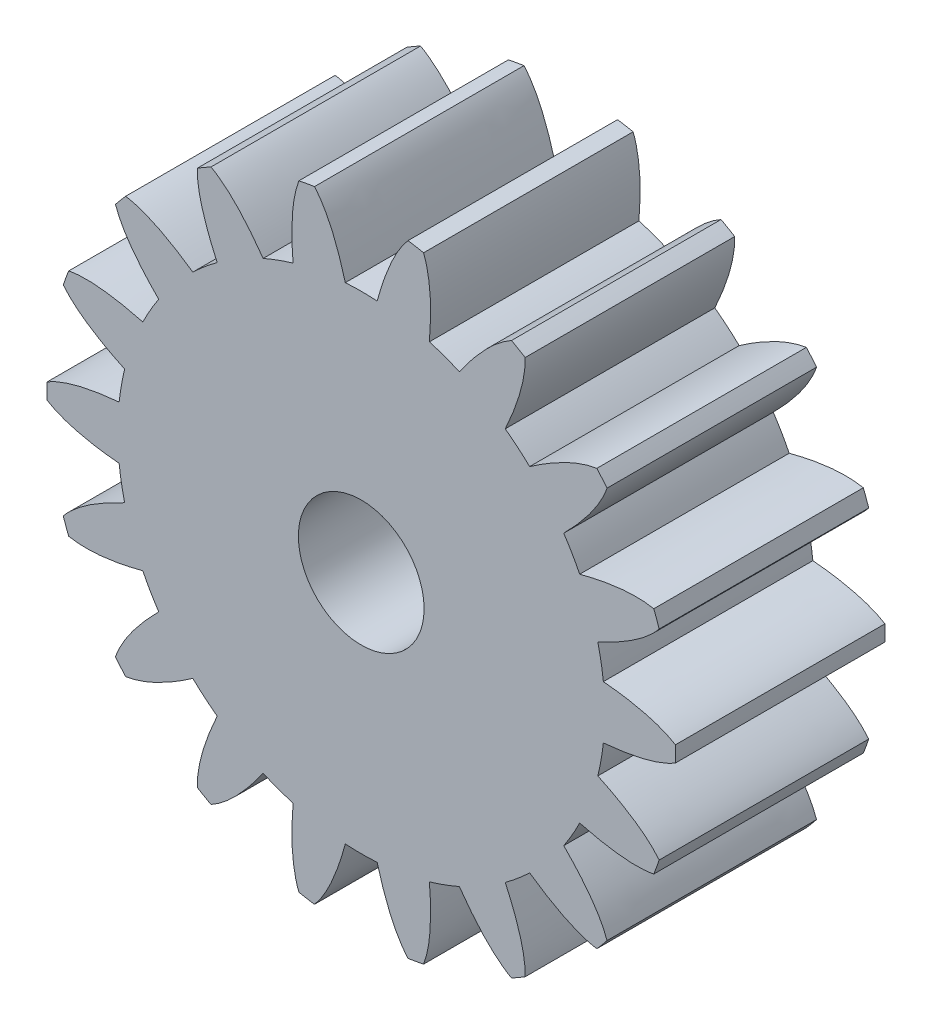
SolidWorks part; units mm, degrees
material "Plain Carbon Steel"
ref_plane "Front Plane" through (0, 0, 0) normal (0, 0, 1) x (1, 0, 0)
ref_plane "Top Plane" through (0, 0, 0) normal (0, 1, 0) x (1, 0, 0)
ref_plane "Right Plane" through (0, 0, 0) normal (1, 0, 0) x (0, 0, -1)
sketch "Sketch2" plane through (0, 0, 0) normal (0, 0, 1) x (1, 0, 0)
  line L0 (-2.6047, 14.7721) -> (-2.0185, 11.4474) construction
  arc A0 (-3.253, 11.1595) -> (-4.6813, 10.6397) centre (0, 0) ccw
  arc A1 (-2.2327, 14.8329) -> (-2.9751, 14.702) centre (0, 0) ccw
  arc A2 (2.9751, 14.702) -> (2.2327, 14.8329) centre (0, 0) ccw
  arc A3 (7.8241, 12.7978) -> (7.1712, 13.1748) centre (0, 0) ccw
  arc A4 (11.7293, 9.35) -> (11.2447, 9.9275) centre (0, 0) ccw
  arc A5 (14.2199, 4.7745) -> (13.962, 5.4829) centre (0, 0) ccw
  arc A6 (14.9953, -0.377) -> (14.9953, 0.377) centre (0, 0) ccw
  arc A7 (13.962, -5.4829) -> (14.2199, -4.7745) centre (0, 0) ccw
  arc A8 (11.2447, -9.9275) -> (11.7293, -9.35) centre (0, 0) ccw
  arc A9 (7.1712, -13.1748) -> (7.8241, -12.7978) centre (0, 0) ccw
  arc A10 (2.2327, -14.8329) -> (2.9751, -14.702) centre (0, 0) ccw
  arc A11 (-2.9751, -14.702) -> (-2.2327, -14.8329) centre (0, 0) ccw
  arc A12 (-7.8241, -12.7978) -> (-7.1712, -13.1748) centre (0, 0) ccw
  arc A13 (-11.7293, -9.35) -> (-11.2447, -9.9275) centre (0, 0) ccw
  arc A14 (-14.2199, -4.7745) -> (-13.962, -5.4829) centre (0, 0) ccw
  arc A15 (-14.9953, 0.377) -> (-14.9953, -0.377) centre (0, 0) ccw
  arc A16 (-13.962, 5.4829) -> (-14.2199, 4.7745) centre (0, 0) ccw
  arc A17 (-11.2447, 9.9275) -> (-11.7293, 9.35) centre (0, 0) ccw
  arc A18 (-7.1712, 13.1748) -> (-7.8241, 12.7978) centre (0, 0) ccw
  arc A19 (-6.8736, 9.374) -> (-8.038, 8.3969) centre (0, 0) ccw
  arc A20 (-9.6652, 6.4577) -> (-10.4251, 5.1414) centre (0, 0) ccw
  arc A21 (-11.2909, 2.7626) -> (-11.5549, 1.2657) centre (0, 0) ccw
  arc A22 (-11.5549, -1.2657) -> (-11.2909, -2.7626) centre (0, 0) ccw
  arc A23 (-10.4251, -5.1414) -> (-9.6652, -6.4577) centre (0, 0) ccw
  arc A24 (-8.038, -8.3969) -> (-6.8736, -9.374) centre (0, 0) ccw
  arc A25 (-4.6813, -10.6397) -> (-3.253, -11.1595) centre (0, 0) ccw
  arc A26 (-0.76, -11.5991) -> (0.76, -11.5991) centre (0, 0) ccw
  arc A27 (3.253, -11.1595) -> (4.6813, -10.6397) centre (0, 0) ccw
  arc A28 (6.8736, -9.374) -> (8.038, -8.3969) centre (0, 0) ccw
  arc A29 (9.6652, -6.4577) -> (10.4251, -5.1414) centre (0, 0) ccw
  arc A30 (11.2909, -2.7626) -> (11.5549, -1.2657) centre (0, 0) ccw
  arc A31 (11.5549, 1.2657) -> (11.2909, 2.7626) centre (0, 0) ccw
  arc A32 (10.4251, 5.1414) -> (9.6652, 6.4577) centre (0, 0) ccw
  arc A33 (8.038, 8.3969) -> (6.8736, 9.374) centre (0, 0) ccw
  arc A34 (4.6813, 10.6397) -> (3.253, 11.1595) centre (0, 0) ccw
  arc A35 (0.76, 11.5991) -> (-0.76, 11.5991) centre (0, 0) ccw
  circle A36 centre (0, 0) radius 3
  spline S0 degree 2 poles (-2.9751, 14.702) (-3.4475, 13.4911) (-3.253, 11.1595) knots 0 0 0 0.715421 0.715421 0.715421
  spline S1 degree 2 poles (-2.2327, 14.8329) (-1.3746, 13.8566) (-0.76, 11.5991) knots 0 0 0 0.715421 0.715421 0.715421
  spline S2 degree 2 poles (2.2327, 14.8329) (1.3746, 13.8566) (0.76, 11.5991) knots 0 0 0 0.715421 0.715421 0.715421
  spline S3 degree 2 poles (2.9751, 14.702) (3.4475, 13.4911) (3.253, 11.1595) knots 0 0 0 0.715421 0.715421 0.715421
  spline S4 degree 2 poles (7.1712, 13.1748) (6.031, 12.5508) (4.6813, 10.6397) knots 0 0 0 0.715421 0.715421 0.715421
  spline S5 degree 2 poles (7.8241, 12.7978) (7.8538, 11.4984) (6.8736, 9.374) knots 0 0 0 0.715421 0.715421 0.715421
  spline S6 degree 2 poles (11.2447, 9.9275) (9.9599, 9.7312) (8.038, 8.3969) knots 0 0 0 0.715421 0.715421 0.715421
  spline S7 degree 2 poles (11.7293, 9.35) (11.3129, 8.1188) (9.6652, 6.4577) knots 0 0 0 0.715421 0.715421 0.715421
  spline S8 degree 2 poles (13.962, 5.4829) (12.6875, 5.7378) (10.4251, 5.1414) knots 0 0 0 0.715421 0.715421 0.715421
  spline S9 degree 2 poles (14.2199, 4.7745) (13.4074, 3.7599) (11.2909, 2.7626) knots 0 0 0 0.715421 0.715421 0.715421
  spline S10 degree 2 poles (14.9953, 0.377) (13.8848, 1.0524) (11.5549, 1.2657) knots 0 0 0 0.715421 0.715421 0.715421
  spline S11 degree 2 poles (14.9953, -0.377) (13.8848, -1.0524) (11.5549, -1.2657) knots 0 0 0 0.715421 0.715421 0.715421
  spline S12 degree 2 poles (14.2199, -4.7745) (13.4074, -3.7599) (11.2909, -2.7626) knots 0 0 0 0.715421 0.715421 0.715421
  spline S13 degree 2 poles (13.962, -5.4829) (12.6875, -5.7378) (10.4251, -5.1414) knots 0 0 0 0.715421 0.715421 0.715421
  spline S14 degree 2 poles (11.7293, -9.35) (11.3129, -8.1188) (9.6652, -6.4577) knots 0 0 0 0.715421 0.715421 0.715421
  spline S15 degree 2 poles (11.2447, -9.9275) (9.9599, -9.7312) (8.038, -8.3969) knots 0 0 0 0.715421 0.715421 0.715421
  spline S16 degree 2 poles (7.8241, -12.7978) (7.8538, -11.4984) (6.8736, -9.374) knots 0 0 0 0.715421 0.715421 0.715421
  spline S17 degree 2 poles (7.1712, -13.1748) (6.031, -12.5508) (4.6813, -10.6397) knots 0 0 0 0.715421 0.715421 0.715421
  spline S18 degree 2 poles (2.9751, -14.702) (3.4475, -13.4911) (3.253, -11.1595) knots 0 0 0 0.715421 0.715421 0.715421
  spline S19 degree 2 poles (2.2327, -14.8329) (1.3746, -13.8566) (0.76, -11.5991) knots 0 0 0 0.715421 0.715421 0.715421
  spline S20 degree 2 poles (-2.2327, -14.8329) (-1.3746, -13.8566) (-0.76, -11.5991) knots 0 0 0 0.715421 0.715421 0.715421
  spline S21 degree 2 poles (-2.9751, -14.702) (-3.4475, -13.4911) (-3.253, -11.1595) knots 0 0 0 0.715421 0.715421 0.715421
  spline S22 degree 2 poles (-7.1712, -13.1748) (-6.031, -12.5508) (-4.6813, -10.6397) knots 0 0 0 0.715421 0.715421 0.715421
  spline S23 degree 2 poles (-7.8241, -12.7978) (-7.8538, -11.4984) (-6.8736, -9.374) knots 0 0 0 0.715421 0.715421 0.715421
  spline S24 degree 2 poles (-11.2447, -9.9275) (-9.9599, -9.7312) (-8.038, -8.3969) knots 0 0 0 0.715421 0.715421 0.715421
  spline S25 degree 2 poles (-11.7293, -9.35) (-11.3129, -8.1188) (-9.6652, -6.4577) knots 0 0 0 0.715421 0.715421 0.715421
  spline S26 degree 2 poles (-13.962, -5.4829) (-12.6875, -5.7378) (-10.4251, -5.1414) knots 0 0 0 0.715421 0.715421 0.715421
  spline S27 degree 2 poles (-14.2199, -4.7745) (-13.4074, -3.7599) (-11.2909, -2.7626) knots 0 0 0 0.715421 0.715421 0.715421
  spline S28 degree 2 poles (-14.9953, -0.377) (-13.8848, -1.0524) (-11.5549, -1.2657) knots 0 0 0 0.715421 0.715421 0.715421
  spline S29 degree 2 poles (-14.9953, 0.377) (-13.8848, 1.0524) (-11.5549, 1.2657) knots 0 0 0 0.715421 0.715421 0.715421
  spline S30 degree 2 poles (-14.2199, 4.7745) (-13.4074, 3.7599) (-11.2909, 2.7626) knots 0 0 0 0.715421 0.715421 0.715421
  spline S31 degree 2 poles (-13.962, 5.4829) (-12.6875, 5.7378) (-10.4251, 5.1414) knots 0 0 0 0.715421 0.715421 0.715421
  spline S32 degree 2 poles (-11.7293, 9.35) (-11.3129, 8.1188) (-9.6652, 6.4577) knots 0 0 0 0.715421 0.715421 0.715421
  spline S33 degree 2 poles (-11.2447, 9.9275) (-9.9599, 9.7312) (-8.038, 8.3969) knots 0 0 0 0.715421 0.715421 0.715421
  spline S34 degree 2 poles (-7.8241, 12.7978) (-7.8538, 11.4984) (-6.8736, 9.374) knots 0 0 0 0.715421 0.715421 0.715421
  spline S35 degree 2 poles (-7.1712, 13.1748) (-6.031, 12.5508) (-4.6813, 10.6397) knots 0 0 0 0.715421 0.715421 0.715421
  dimension "D1" = 6
extrude "Boss-Extrude1" add sketch "Sketch2" along normal blind 10
